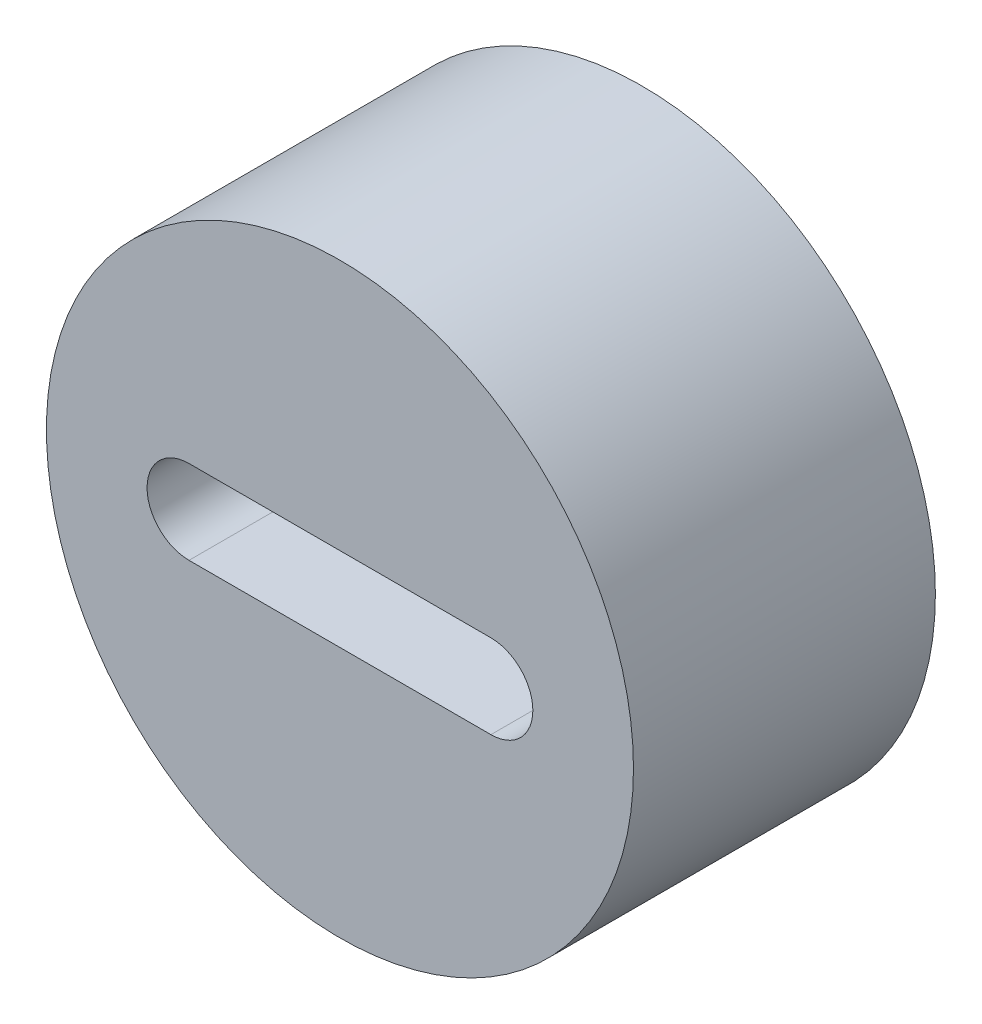
SolidWorks part; units mm, degrees
ref_plane "Piano frontale" through (0, 0, 0) normal (0, 0, 1) x (1, 0, 0)
ref_plane "Piano superiore" through (0, 0, 0) normal (0, 1, 0) x (1, 0, 0)
ref_plane "Piano destro" through (0, 0, 0) normal (1, 0, 0) x (0, 0, -1)
sketch "Schizzo1" plane through (0, 0, 0) normal (0, 0, 1) x (1, 0, 0)
  line L0 (-9, 0) -> (9, 0) construction
  line L1 (-9, 2.5) -> (9, 2.5)
  line L2 (-9, -2.5) -> (9, -2.5)
  line L3 (-17.5, 0) -> (17.5, 0) construction
  circle A0 centre (0, 0) radius 17.5
  arc A1 (-9, 2.5) -> (-9, -2.5) centre (-9, 0) ccw
  arc A2 (9, -2.5) -> (9, 2.5) centre (9, 0) ccw
  point P5 (0, 0)
  point P12 (0, 0)
  point P13 (0, 0)
  point P14 (9.4949, 0)
  dimension "D1" = 35
  dimension "D2" = 18
  dimension "D3" = 5
extrude "Estrusione-Estrusione1" add sketch "Schizzo1" along normal blind 18
